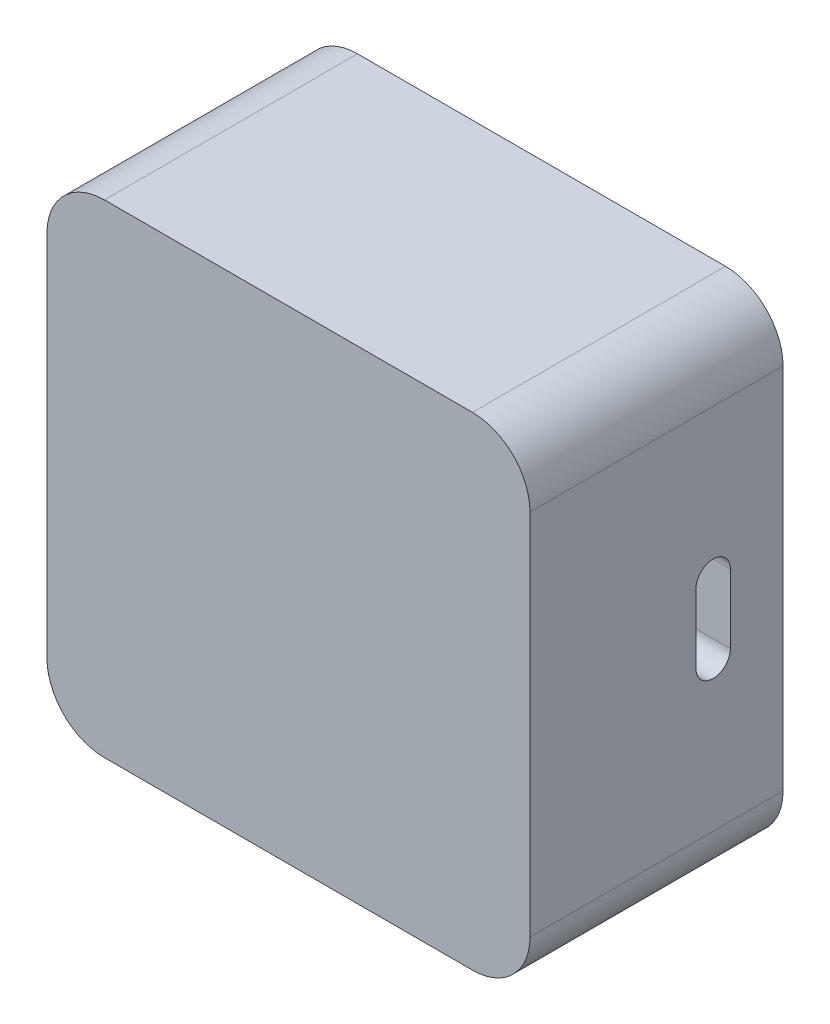
SolidWorks part; units mm, degrees
ref_plane "前视基准面" through (0, 0, 0) normal (0, 0, 1) x (1, 0, 0)
ref_plane "上视基准面" through (0, 0, 0) normal (0, 1, 0) x (1, 0, 0)
ref_plane "右视基准面" through (0, 0, 0) normal (1, 0, 0) x (0, 0, -1)
sketch "草图1" plane through (0, 0, 0) normal (0, 0, 1) x (1, 0, 0)
  line L0 (0, 0) -> (50000, 0) construction
  line L1 (0, 0) -> (0, 50000) construction
  line L3 (-21, 21) -> (21, 21)
  line L4 (-21, 21) -> (-21, -21)
  line L5 (-21, -21) -> (21, -21)
  line L6 (21, 21) -> (21, -21)
extrude "凸台-拉伸1" add sketch "草图1" along normal blind 22
sketch "草图2" plane through (21, 0, 0) normal (1, 0, 0) x (0, 0, -1)
  line L0 (-11, -21) -> (-11, 49979) construction
  line L1 (-22, -21) -> (0, -21) construction
  line L2 (-22, 0) -> (49978, 0) construction
  line L3 (-22, -21) -> (-22, 21) construction
  line L4 (0, 0) -> (-23200.3497, 44291.5768) construction
  line L5 (-22, 21) -> (0, 21) construction
  line L6 (0, 21) -> (-23200.3497, -44270.5768) construction
  line L7 (-6.0751, 10.9993) -> (-6.0751, 50010.9993) construction
  line L9 (-7.5751, 4.5) -> (-4.5751, 4.5)
  line L10 (-7.5751, 4.5) -> (-7.5751, -4.5)
  line L11 (-7.5751, -4.5) -> (-4.5751, -4.5)
  line L12 (-4.5751, 4.5) -> (-4.5751, -4.5)
  circle A0 centre (-6.0751, 3) radius 1.5
  circle A1 centre (-6.0751, -3) radius 1.5
  point P4 (-11, -21)
  point P9 (-22, 0)
  point P15 (-11, 21)
extrude "切除-拉伸1" cut sketch "草图2" against normal blind 7 contours A0 | L10 A1 L12 A0 | A1
sketch "草图3" plane through (0, -21, 0) normal (0, -1, 0) x (1, 0, 0)
  line L0 (-21, 22) -> (44270.5768, -23178.3497) construction
  line L1 (21, 22) -> (-44270.5768, -23178.3497) construction
  line L2 (0, 0) -> (0, 50000) construction
  line L3 (-21, 0) -> (21, 0) construction
  line L4 (0, 11) -> (50000, 11) construction
  circle A0 centre (0, 11) radius 4
  point P12 (0, 0)
extrude "切除-拉伸2" cut sketch "草图3" against normal blind 10
fillet "圆角1" radius 5 4 edges at (-21, 21, 11) (-21, -21, 11) (21, -21, 11) (21, 21, 11)
